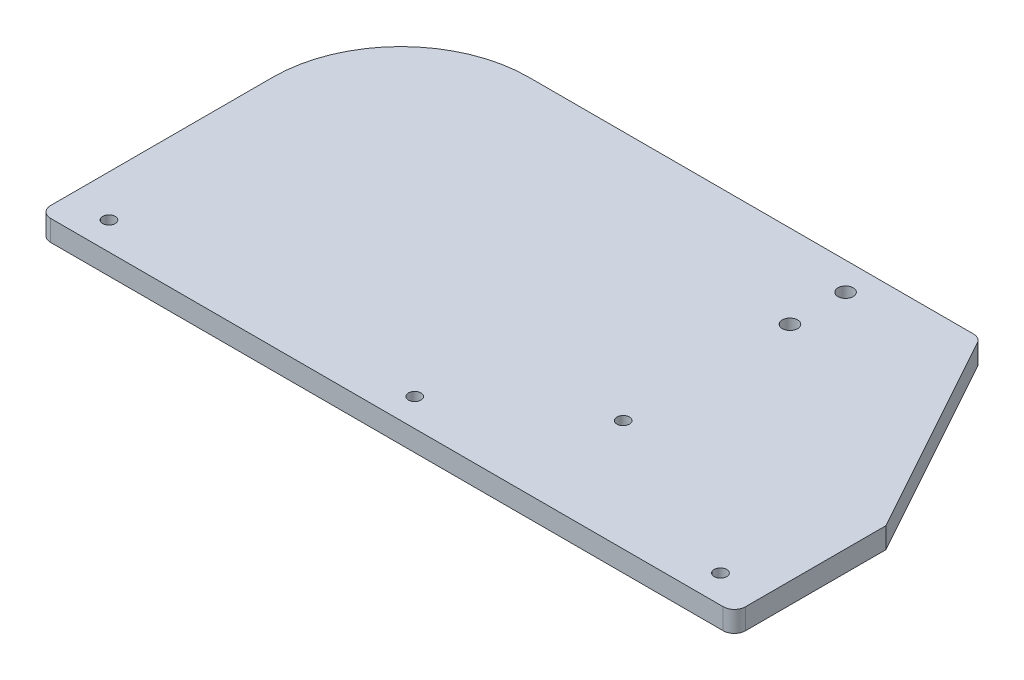
SolidWorks part; units mm, degrees
ref_plane "Front Plane" through (0, 0, 0) normal (0, 0, 1) x (1, 0, 0)
ref_plane "Top Plane" through (0, 0, 0) normal (0, 1, 0) x (1, 0, 0)
ref_plane "Right Plane" through (0, 0, 0) normal (1, 0, 0) x (0, 0, -1)
sketch "Sketch1" plane through (0, 0, 0) normal (0, 1, 0) x (1, 0, 0)
  line L0 (-170, 0) -> (80, 0) construction
  line L1 (0, -10) -> (0, 120) construction
  line L2 (-166, -10) -> (76, -10)
  line L3 (80, -6) -> (80, 44.5)
  line L4 (80, 44.5) -> (39.5026, 117.9317)
  line L5 (36, 120) -> (-124, 120)
  line L6 (-170, 74) -> (-170, -6)
  arc A0 (76, -10) -> (80, -6) centre (76, -6) ccw
  arc A1 (39.5026, 117.9317) -> (36, 120) centre (36, 116) ccw
  arc A2 (-124, 120) -> (-170, 74) centre (-124, 74) ccw
  arc A3 (-170, -6) -> (-166, -10) centre (-166, -6) ccw
  circle A4 centre (0, 30) radius 2 construction
  circle A5 centre (65, 0) radius 2.25
  circle A6 centre (-45, 0) radius 2.25
  circle A7 centre (-155, 0) radius 2.25
  circle A8 centre (0, 90) radius 2.75
  circle A9 centre (0, 110) radius 2.5 construction
  circle A10 centre (0, 110) radius 2.75
  circle A11 centre (0, 30) radius 2.25
  point P28 (0, 39.8245)
  point P50 (0, 67.167)
  dimension "D3" = 5
  dimension "D4" = 4
  dimension "D10" = 4
  dimension "D6" = 130
  dimension "D13" = 160
  dimension "D14" = 54.5
  dimension "D15" = 80
  dimension "D5" = 10
  dimension "D7" = 30
  dimension "D8" = 60
  dimension "D9" = 20
  dimension "D11" = 65
  dimension "D12" = 45
  dimension "D16" = 110
  dimension "D17" = 250
  dimension "D18" = 15
  dimension "D19" = 15
  dimension "D20" = 10
  dimension "D1" = 0.25
  dimension "D2" = 0.25
extrude "Boss-Extrude1" add sketch "Sketch1" along normal blind 7.5
equation "\"Tolerance\"=0.25"
equation "\"D1@Sketch1\"=\"Tolerance\""
equation "\"D2@Sketch1\"=\"Tolerance\""
